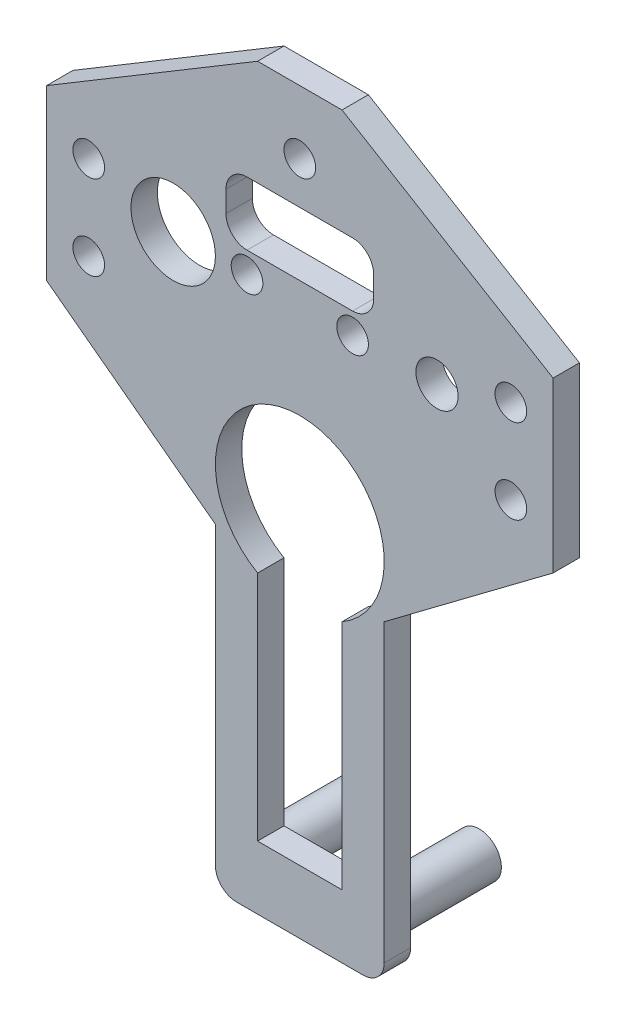
SolidWorks part; units mm, degrees
ref_plane "Front Plane" through (0, 0, 0) normal (0, 0, 1) x (1, 0, 0)
ref_plane "Top Plane" through (0, 0, 0) normal (0, 1, 0) x (1, 0, 0)
ref_plane "Right Plane" through (0, 0, 0) normal (1, 0, 0) x (0, 0, -1)
sketch "Sketch1" plane through (0, 0, 0) normal (0, 0, 1) x (1, 0, 0)
  line L0 (-24, 7.0718) -> (-24, 23.0718)
  line L1 (-24, 23.0718) -> (-4, 35.0718)
  line L2 (-4, 35.0718) -> (4, 35.0718)
  line L3 (4, 35.0718) -> (24, 23.0718)
  line L4 (24, 23.0718) -> (24, 7.0718)
  line L5 (24, 7.0718) -> (8, -4.9282)
  line L6 (8, -4.9282) -> (8, -32.9282)
  line L7 (-6, -34.9282) -> (6, -34.9282)
  line L8 (-8, -32.9282) -> (-8, -4.9282)
  line L9 (-8, -4.9282) -> (-24, 7.0718)
  line L10 (4, -28.9282) -> (-4, -28.9282)
  line L11 (-4, -28.9282) -> (-4, -6.9282)
  line L12 (4, -6.9282) -> (4, -28.9282)
  line L13 (-5, 25.0718) -> (5, 25.0718)
  line L14 (7, 23.0718) -> (7, 21.0718)
  line L15 (-7, 23.0718) -> (-7, 21.0718)
  line L16 (-5, 19.0718) -> (5, 19.0718)
  line L17 (0, 35.0718) -> (0, 10) construction
  arc A0 (-4, -6.9282) -> (4, -6.9282) centre (0, 0) cw
  arc A1 (5, 25.0718) -> (7, 23.0718) centre (5, 23.0718) cw
  arc A2 (-5, 25.0718) -> (-7, 23.0718) centre (-5, 23.0718) ccw
  arc A3 (-7, 21.0718) -> (-5, 19.0718) centre (-5, 21.0718) ccw
  arc A4 (5, 19.0718) -> (7, 21.0718) centre (5, 21.0718) ccw
  circle A5 centre (-12, 17.0718) radius 4
  circle A6 centre (-5, 17.0718) radius 1.5
  circle A7 centre (5, 17.0718) radius 1.5
  circle A8 centre (0, 29.0718) radius 1.5
  circle A9 centre (20, 19.0718) radius 1.5
  circle A10 centre (20, 11.0718) radius 1.5
  circle A11 centre (-20, 19.0718) radius 1.5
  circle A12 centre (-20, 11.0718) radius 1.5
  circle A13 centre (13, 17.0718) radius 2
  arc A14 (-8, -32.9282) -> (-6, -34.9282) centre (-6, -32.9282) ccw
  arc A15 (6, -34.9282) -> (8, -32.9282) centre (6, -32.9282) ccw
  dimension "D1" = 28
  dimension "D4" = 12
  dimension "D7" = 4
  dimension "D8" = 4
  dimension "D9" = 2
  dimension "D10" = 8
  dimension "D19" = 8
  dimension "D20" = 10
  dimension "D22" = 2
  dimension "D18" = 8
  dimension "D24" = 3
  dimension "D25" = 4
  dimension "D31" = 4
  dimension "D3" = 8
  dimension "D5" = 10
  dimension "D6" = 22
  dimension "D11" = 6
  dimension "D12" = 16
  dimension "D13" = 17
  dimension "D14" = 20
  dimension "D15" = 48
  dimension "D16" = 24
  dimension "D17" = 10
  dimension "D21" = 2
  dimension "D23" = 12
  dimension "D26" = 4
  dimension "D27" = 4
  dimension "D28" = 4
  dimension "D29" = 2
  dimension "D30" = 6
  dimension "D32" = 5
  dimension "D33" = 70
  dimension "D34" = 24
  dimension "D35" = 120.964
  dimension "D36" = 11
extrude "Boss-Extrude1" add sketch "Sketch1" along normal blind 2.5
sketch "Sketch2" plane through (0, 0, 0) normal (0, 0, -1) x (-1, 0, 0)
  line L0 (-5, -31.5282) -> (5, -31.5282) construction
  line L1 (6, -34.9282) -> (-6, -34.9282) construction
  circle A0 centre (-5, -31.5282) radius 2.1
  circle A2 centre (5, -31.5282) radius 2.1
  dimension "D1" = 3.4
extrude "Boss-Extrude2" add sketch "Sketch2" along normal blind 9.5
sketch "Sketch4" plane through (0, 0, -9.5) normal (0, 0, -1) x (-1, 0, 0)
  circle A0 centre (-5, -31.5282) radius 1.5
  circle A1 centre (5, -31.5282) radius 1.5
  dimension "D1" = 3
extrude "Cut-Extrude1" cut sketch "Sketch4" against normal blind 5
sketch "Sketch5" plane through (0, 0, 0) normal (0, 0, 1) x (1, 0, 0)
  line L1 (-18.5706, -31.4282) -> (18.4732, -31.4282) construction
  line L2 (33.4719, 17.0718) -> (-29.6435, 17.0718) construction
  dimension "D1" = 48.5
